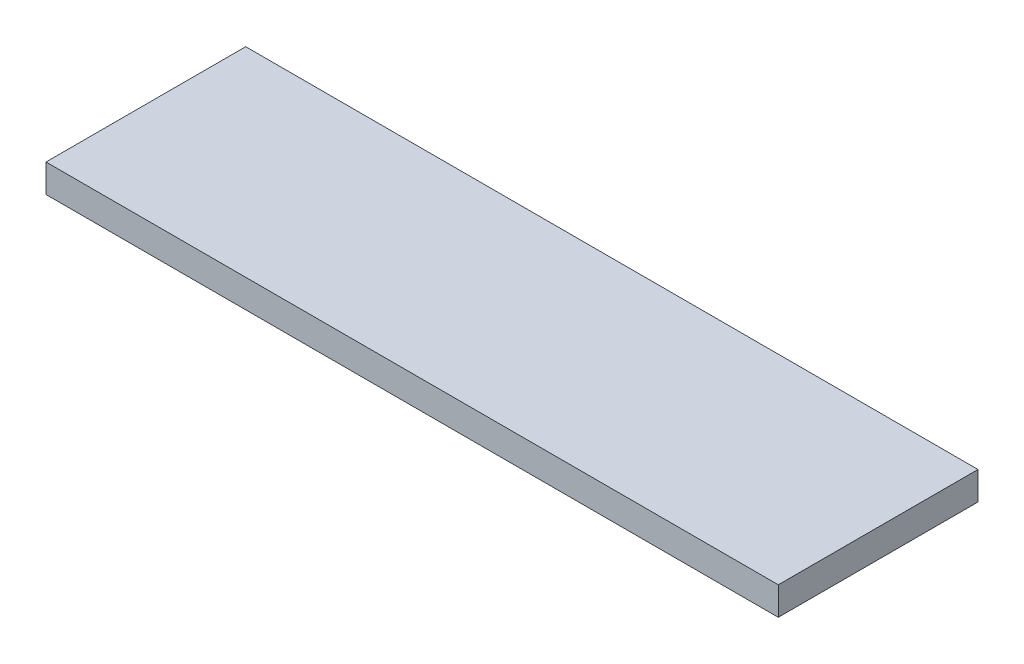
SolidWorks part; units mm, degrees
ref_plane "Front Plane" through (0, 0, 0) normal (0, 0, 1) x (1, 0, 0)
ref_plane "Top Plane" through (0, 0, 0) normal (0, 1, 0) x (1, 0, 0)
ref_plane "Right Plane" through (0, 0, 0) normal (1, 0, 0) x (0, 0, -1)
sketch "Sketch1" plane through (0, 0, 0) normal (0, 1, 0) x (1, 0, 0)
  line L1 (-82.5, -22.5) -> (82.5, -22.5)
  line L2 (-82.5, -22.5) -> (-82.5, 22.5)
  line L3 (-82.5, 22.5) -> (82.5, 22.5)
  line L4 (82.5, -22.5) -> (82.5, 22.5)
  line L5 (-82.5, -22.5) -> (82.5, 22.5) construction
  line L6 (-82.5, 22.5) -> (82.5, -22.5) construction
  point P0 (0, 0)
  dimension "D1" = 45
  dimension "D2" = 165
extrude "Boss-Extrude1" add sketch "Sketch1" along normal blind 6.35
